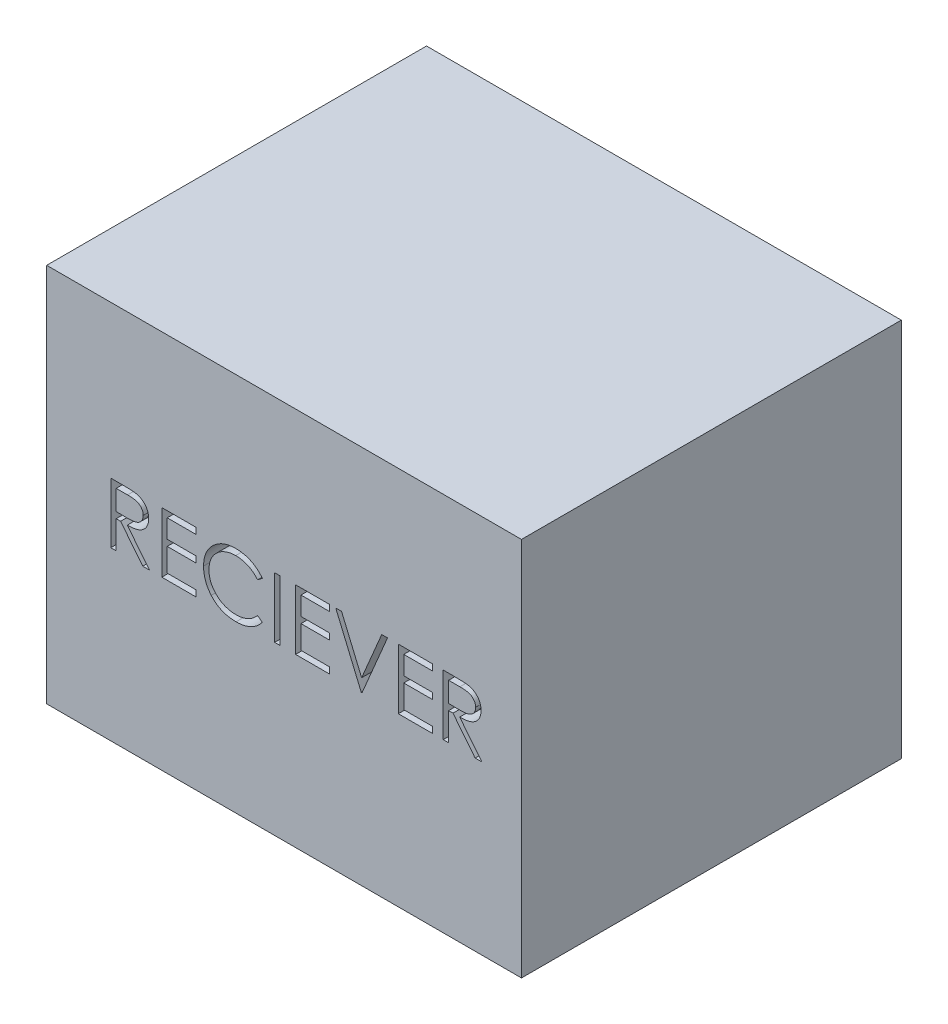
SolidWorks part; units mm, degrees
ref_plane "Front Plane" through (0, 0, 0) normal (0, 0, 1) x (1, 0, 0)
ref_plane "Top Plane" through (0, 0, 0) normal (0, 1, 0) x (1, 0, 0)
ref_plane "Right Plane" through (0, 0, 0) normal (1, 0, 0) x (0, 0, -1)
sketch "Sketch1" plane through (0, 0, 0) normal (1, 0, 0) x (0, 0, -1)
  line L1 (-20, 20) -> (20, 20)
  line L2 (-20, 20) -> (-20, -20)
  line L3 (-20, -20) -> (20, -20)
  line L4 (20, 20) -> (20, -20)
  point P4 (0, 0)
  point P5 (0, 20)
  point P6 (-20, 0)
  point P7 (0, 0)
  point P8 (0, 0)
  point P9 (0, 0)
  point P11 (0, 0)
  dimension "D1" = 40
extrude "Boss-Extrude1" add sketch "Sketch1" along normal mid plane 50 contours L2 L3 L4 L1
sketch "Sketch2" plane through (0, 0, 20) normal (0, 0, 1) x (1, 0, 0)
  text T0 "RECIEVER" font "Century Gothic" height in points 24
  point P1 (-23.8788, -3.4904)
  point P2 (-16.4167, -2.2868)
  point P3 (-19.0645, -2.3831)
extrude "Cut-Extrude1" cut sketch "Sketch2" against normal blind 10
